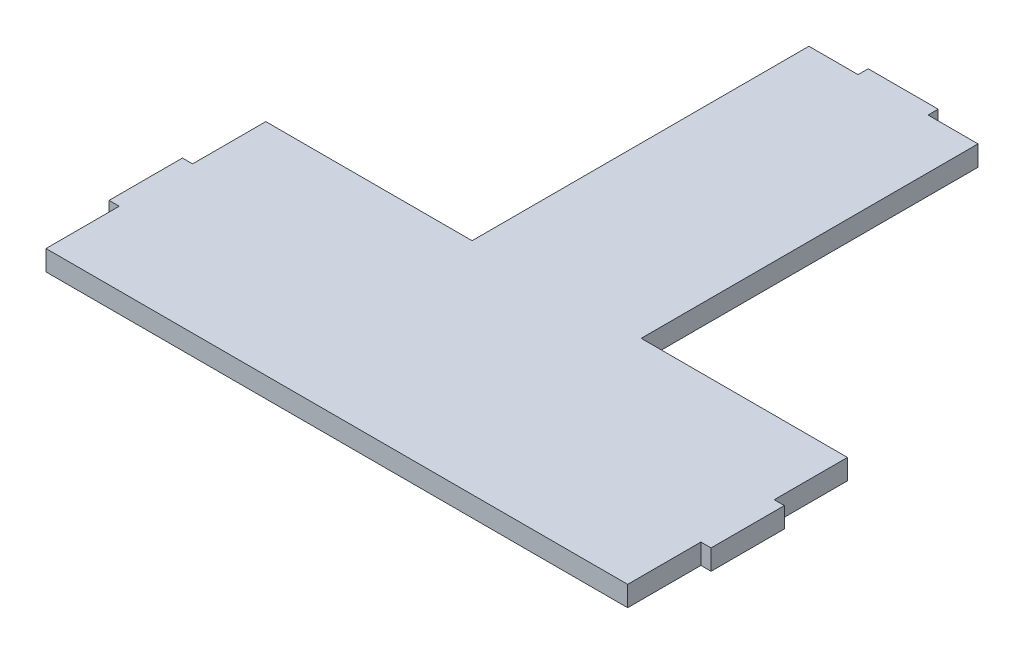
SolidWorks part; units mm, degrees
ref_plane "Front Plane" through (0, 0, 0) normal (0, 0, 1) x (1, 0, 0)
ref_plane "Top Plane" through (0, 0, 0) normal (0, 1, 0) x (1, 0, 0)
ref_plane "Right Plane" through (0, 0, 0) normal (1, 0, 0) x (0, 0, -1)
sketch "Sketch1" plane through (0, 0, 0) normal (0, 1, 0) x (1, 0, 0)
  line L3 (50, -48.6396) -> (50, 50.9604)
  line L5 (0, 50.9604) -> (0, -48.6396)
  line L8 (-64, -91.9796) -> (-61, -91.9796)
  line L9 (-61, -91.9796) -> (-61, -113.6396)
  line L10 (-61, -113.6396) -> (111, -113.6396)
  line L11 (111, -113.6396) -> (111, -91.9796)
  line L12 (111, -91.9796) -> (114, -91.9796)
  line L13 (0, -48.6396) -> (-61, -48.6396)
  line L14 (-61, -48.6396) -> (-61, -70.2996)
  line L15 (-61, -70.2996) -> (-64, -70.2996)
  line L16 (111, -70.2996) -> (114, -70.2996)
  line L17 (111, -70.2996) -> (111, -48.6396)
  line L18 (111, -48.6396) -> (50, -48.6396)
  line L19 (114, -70.2996) -> (114, -91.9796)
  line L20 (-64, -70.2996) -> (-64, -91.9796)
  line L21 (0, 50.9604) -> (14.5331, 50.9604)
  line L22 (14.5331, 50.9604) -> (14.5331, 53.9604)
  line L23 (14.5331, 53.9604) -> (35.2291, 53.9604)
  line L24 (35.2291, 53.9604) -> (35.2291, 50.9604)
  line L25 (35.2291, 50.9604) -> (50, 50.9604)
  dimension "D1" = 178
  dimension "D2" = 50
  dimension "D3" = 65
  dimension "D4" = 3
  dimension "D5" = 3
  dimension "D6" = 102.6
  dimension "D7" = 21.68
extrude "Boss-Extrude1" add sketch "Sketch1" along normal blind 6
